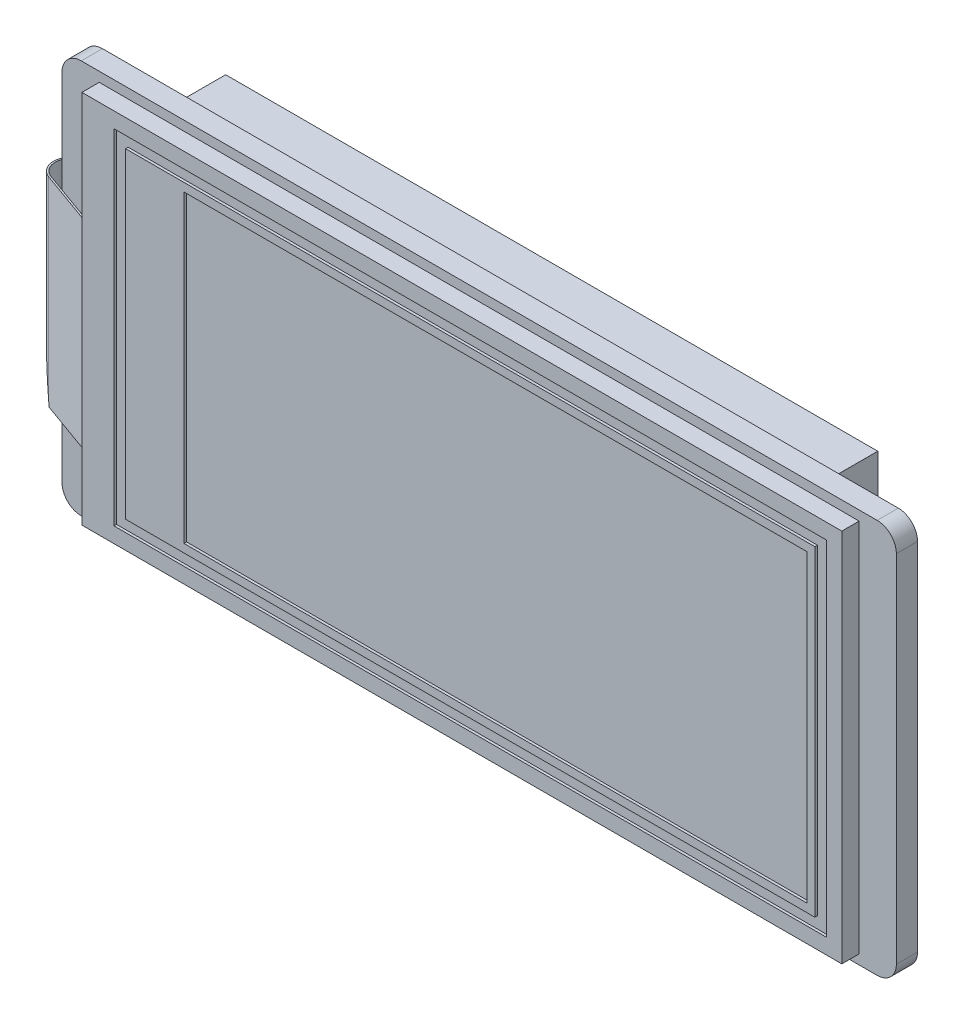
SolidWorks part; units mm, degrees
material "ABS"
ref_plane "Ebene1" through (0, 0, 0) normal (0, 0, 1) x (1, 0, 0)
ref_plane "Ebene2" through (0, 0, 0) normal (0, 1, 0) x (1, 0, 0)
ref_plane "Ebene3" through (0, 0, 0) normal (1, 0, 0) x (0, 0, -1)
sketch "Skizze1" plane through (0, 0, 0) normal (0, 0, 1) x (1, 0, 0)
  line L1 (-32.5, 15.35) -> (32.5, 15.35)
  line L2 (-32.5, 15.35) -> (-32.5, -15.35)
  line L3 (-32.5, -15.35) -> (32.5, -15.35)
  line L4 (32.5, 15.35) -> (32.5, -15.35)
  line L5 (-32.5, 15.35) -> (32.5, -15.35) construction
  line L6 (-32.5, -15.35) -> (32.5, 15.35) construction
  point P0 (0, 0)
  dimension "D1" = 30.7
  dimension "D2" = 65
extrude "Aufsatz-Linear austragen1" add sketch "Skizze1" along normal blind 1.65
fillet "Verrundung1" radius 1.5 4 edges at (-32.5, 15.35, 0.825) (-32.5, -15.35, 0.825) (32.5, -15.35, 0.825) (32.5, 15.35, 0.825)
sketch "Skizze4" plane through (0, 0, 1.65) normal (0, 0, 1) x (1, 0, 0)
  line L0 (-32.5, 13.85) -> (-32.5, -13.85) construction
  line L1 (-34, -7.5) -> (-31, -7.5)
  line L2 (-34, -7.5) -> (-34, 7.5)
  line L3 (-34, 7.5) -> (-31, 7.5)
  line L4 (-31, -7.5) -> (-31, 7.5)
  line L5 (-34, -7.5) -> (-31, 7.5) construction
  line L6 (-34, 7.5) -> (-31, -7.5) construction
  point P0 (-32.5, 0)
  dimension "D1" = 15
  dimension "D2" = 3
extrude "Schnitt-Linear austragen1" [suppressed] cut sketch "Skizze4" against normal through all
sketch "Skizze5" plane through (0, 0, 1.65) normal (0, 0, 1) x (1, 0, 0)
  line L0 (32.5, -13.85) -> (32.5, 13.85) construction
  line L1 (-29.6, 14.6) -> (29.6, 14.6)
  line L2 (-29.6, 14.6) -> (-29.6, -14.6)
  line L3 (-29.6, -14.6) -> (29.6, -14.6)
  line L4 (29.6, 14.6) -> (29.6, -14.6)
  line L5 (-29.6, 14.6) -> (29.6, -14.6) construction
  line L6 (-29.6, -14.6) -> (29.6, 14.6) construction
  line L7 (0, 0) -> (-6.5165, 0) construction
  point P0 (0, 0)
  point P11 (0, 0)
  dimension "D1" = 29.2
  dimension "D2" = 59.2
  dimension "D3" = 2.9
extrude "Aufsatz-Linear austragen2" add sketch "Skizze5" along normal blind 1.35
sketch "Skizze6" plane through (0, 0, 3) normal (0, 0, 1) x (1, 0, 0)
  line L0 (27.5, -12.5) -> (27.5, 13.4) construction
  line L1 (-27.1, -12.5) -> (27.5, -12.5) construction
  line L3 (29.6, -14.6) -> (29.6, 14.6) construction
  line L4 (-29.6, -14.6) -> (29.6, -14.6) construction
  line L6 (-21.65, -11.856) -> (26.9, -11.856)
  line L7 (26.9, -11.856) -> (26.9, 11.854)
  line L8 (26.9, 11.854) -> (-21.65, 11.854)
  line L9 (-21.65, 11.854) -> (-21.65, -11.856)
  line L11 (-29.6, -13.4) -> (29.6, -13.4)
  line L12 (-27.1, -13.4) -> (28.4, -13.4)
  line L13 (-27.1, -13.4) -> (-27.1, 13.4)
  line L14 (28.4, -14.6) -> (28.4, 14.6)
  line L15 (28.4, -13.4) -> (28.4, 13.4)
  line L16 (-27.1, 13.4) -> (28.4, 13.4)
  line L17 (-26.2, -12.5) -> (27.5, -12.5)
  line L18 (27.5, -12.5) -> (27.5, 12.5)
  line L19 (-26.2, -12.5) -> (-26.2, 12.5)
  line L20 (27.5, 12.5) -> (-26.2, 12.5)
  dimension "D2" = 48.55
  dimension "D1" = 2.7
  dimension "D3" = 2.744
  dimension "D4" = 23.71
  dimension "D7" = 55.5
  dimension "D8" = 26.8
  dimension "D10" = 53.7
  dimension "D11" = 25
  dimension "D5" = 1.2
  dimension "D6" = 1.2
  dimension "D9" = 0.9
sketch "Skizze7" plane through (0, 0, 0) normal (0, 1, 0) x (1, 0, 0)
  line L0 (-29.6, -3) -> (-33.6282, -1.5551)
  line L1 (-29.5, 0) -> (-29.5, 1)
  line L2 (31, 0) -> (-31, 0) construction
  line L3 (-29.5, 1) -> (-33.1838, 1)
  line L4 (-32.5, -1.65) -> (-32.5, 0) construction
  line L5 (-29.63, 0) -> (-29.63, 0.87)
  line L6 (-29.63, 0.87) -> (-33.1838, 0.87)
  line L7 (-29.6, -2.8619) -> (-33.5843, -1.4327)
  line L8 (-29.6, -3) -> (-29.6, -1.65) construction
  line L9 (-29.6, -3) -> (-29.6, -2.8619)
  line L10 (-29.5561, -2.8776) -> (-33.5843, -1.4327) construction
  line L11 (-29.5, 0) -> (-29.63, 0)
  arc A0 (-33.1838, 1) -> (-33.6282, -1.5551) centre (-33.1838, -0.3162) ccw
  arc A1 (-33.1838, 0.87) -> (-33.5843, -1.4327) centre (-33.1838, -0.3162) ccw
  dimension "D3" = 2
  dimension "D4" = 1.3162
  dimension "D1" = 3
  dimension "D2" = 1
  dimension "D5" = 0.13
extrude "Aufsatz-Linear austragen4" add sketch "Skizze7" along normal blind 6.16 and the other way blind 9.35
sketch "Skizze8" plane through (0, 0, -1) normal (0, 0, -1) x (-1, 0, 0)
  line L0 (29.5, 6.16) -> (33.1838, 6.16) construction
  line L1 (28.4642, -6.34) -> (35.7527, -6.34)
  line L2 (28.4642, -6.34) -> (28.4642, -12.4294)
  line L3 (28.4642, -12.4294) -> (35.7527, -12.4294)
  line L4 (35.7527, -6.34) -> (35.7527, -12.4294)
  line L5 (28.4642, -6.34) -> (35.7527, -12.4294) construction
  line L6 (28.4642, -12.4294) -> (35.7527, -6.34) construction
  point P4 (32.1084, -9.3847)
  dimension "D1" = 12.5
extrude "Schnitt-Linear austragen2" cut sketch "Skizze8" against normal blind 1
sketch "Skizze9" plane through (0, 0, -1) normal (0, 0, -1) x (-1, 0, 0)
  line L0 (33.1838, -6.34) -> (34.4615, -6.34) construction
  line L1 (34.5, -9.35) -> (34.5, 6.16) construction
  line L2 (33.5843, -9.35) -> (34.37, -9.35) construction
  line L3 (33.9877, -6.34) -> (34.5, -6.34)
  line L4 (34.5, -9.35) -> (34.5, -6.34)
  line L5 (33.5843, -9.35) -> (34.5, -9.35)
  line L6 (33.5843, -9.35) -> (33.9877, -6.34)
extrude "Schnitt-Linear austragen4" cut sketch "Skizze9" against normal through all
sketch "Skizze10" plane through (0, 0, 0) normal (0, 0, -1) x (-1, 0, 0)
  line L0 (31, -15.35) -> (-31, -15.35) construction
  line L1 (10, -15.35) -> (-10, -15.35)
  line L2 (10, -15.35) -> (10, -7.85)
  line L3 (10, -7.85) -> (-10, -7.85)
  line L4 (-10, -15.35) -> (-10, -7.85)
  line L5 (10, -15.35) -> (-10, -7.85) construction
  line L6 (10, -7.85) -> (-10, -15.35) construction
  line L7 (32.5, 13.85) -> (32.5, -13.85) construction
  point P4 (0, -11.6)
  dimension "D1" = 22.5
  dimension "D2" = 20
  dimension "D3" = 7.5
extrude "Aufsatz-Linear austragen5" add sketch "Skizze10" along normal blind 5.5
sketch "Skizze11" plane through (0, 0, 0) normal (0, 0, -1) x (-1, 0, 0)
  line L1 (25.4, 14.39) -> (-25.4, 14.39)
  line L2 (25.4, 14.39) -> (25.4, 9.31)
  line L3 (25.4, 9.31) -> (-25.4, 9.31)
  line L4 (-25.4, 14.39) -> (-25.4, 9.31)
  line L5 (25.4, 14.39) -> (-25.4, 9.31) construction
  line L6 (25.4, 9.31) -> (-25.4, 14.39) construction
  line L8 (-32.5, -13.85) -> (-32.5, 13.85) construction
  line L9 (-31, 15.35) -> (31, 15.35) construction
  point P4 (0, 11.85)
  dimension "D1" = 50.8
  dimension "D2" = 32.5
  dimension "D3" = 5.08
  dimension "D4" = 3.5
extrude "Aufsatz-Linear austragen6" add sketch "Skizze11" along normal blind 4
sketch "Skizze12" plane through (0, 0, 0) normal (0, 0, -1) x (-1, 0, 0)
  line L0 (29.5, -6.34) -> (29.5, 6.16) construction
  line L1 (32.5, 13.85) -> (32.5, -13.85) construction
  line L2 (29.5, 8.6) -> (25.5, 8.6)
  line L3 (29.5, 8.6) -> (29.5, -8.6)
  line L4 (29.5, -8.6) -> (25.5, -8.6)
  line L5 (25.5, 8.6) -> (25.5, -8.6)
  line L6 (29.5, 8.6) -> (25.5, -8.6) construction
  line L7 (29.5, 0) -> (22.9124, 0) construction
  line L8 (29.5, -8.6) -> (25.5, 8.6) construction
  point P4 (27.5, 0)
  dimension "D1" = 17.2
  dimension "D2" = 7
extrude "Aufsatz-Linear austragen8" add sketch "Skizze12" along normal blind 2
extrude "Schnitt-Linear austragen5" cut sketch "Skizze6" against normal blind 0.2 contours L8 L9 L6 L7 | L16 L13 L12 L15 L20 L18 L17 L19
sketch "Skizze14" plane through (0, 0, -4) normal (0, 0, -1) x (-1, 0, 0)
  line L0 (-25.4, 11.85) -> (-22.1394, 11.85) construction
  line L1 (-25.4, 14.39) -> (-25.4, 9.31) construction
  line L2 (-25.4, 14.39) -> (-25.4, 9.31) construction
  line L4 (-23.78, 13.47) -> (-24.48, 13.47)
  line L5 (-24.48, 13.47) -> (-24.48, 12.77)
  line L6 (-24.48, 12.77) -> (-23.78, 12.77)
  line L7 (-23.78, 12.77) -> (-23.78, 13.47)
  line L8 (-23.78, 10.93) -> (-24.48, 10.93)
  line L9 (-24.48, 10.93) -> (-24.48, 10.23)
  line L10 (-24.48, 10.23) -> (-23.78, 10.23)
  line L11 (-23.78, 10.23) -> (-23.78, 10.93)
  circle A2 centre (-24.13, 13.12) radius 0.35 construction
  circle A3 centre (-24.13, 10.58) radius 0.35 construction
  dimension "D2" = 0.7
  dimension "D1" = 2.54
  dimension "D3" = 1.27
  dimension "D4" = 0.7
extrude "Schnitt-Linear austragen6" cut sketch "Skizze14" against normal blind 4
pattern_linear "Lineares Muster1" count 20 spacing 2.54 along (-1, 0, 0) of "Schnitt-Linear austragen6"
